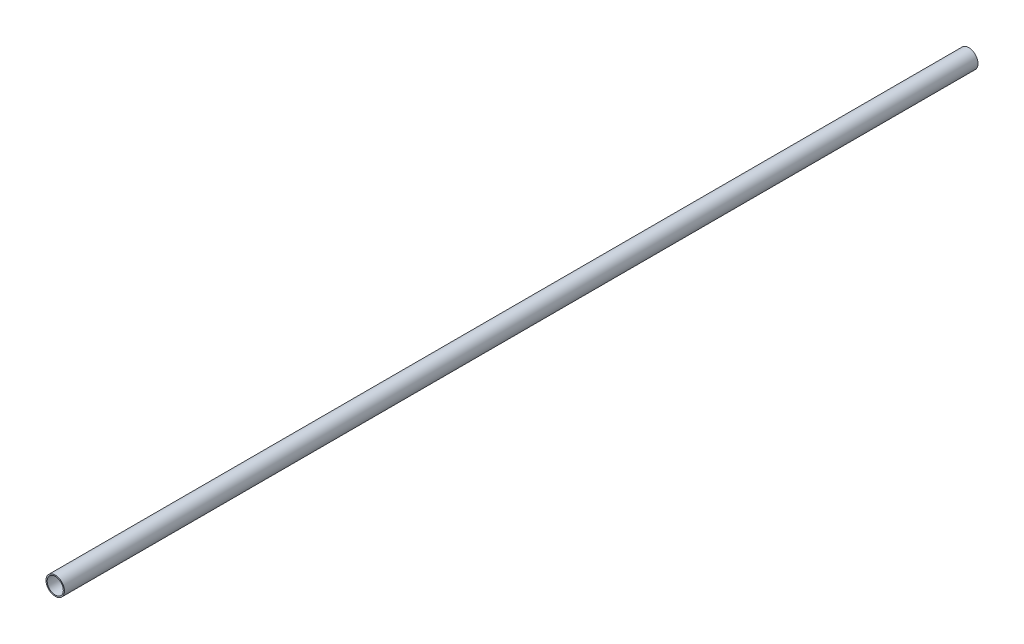
SolidWorks part; units mm, degrees
material "AISI Type 316L stainless steel"
ref_plane "Front Plane" through (0, 0, 0) normal (0, 0, 1) x (1, 0, 0)
ref_plane "Top Plane" through (0, 0, 0) normal (0, 1, 0) x (1, 0, 0)
ref_plane "Right Plane" through (0, 0, 0) normal (1, 0, 0) x (0, 0, -1)
sketch "Extrude sketch 1" plane through (0, 0, 0) normal (0, 0, 1) x (1, 0, 0)
  circle A0 centre (0, 0) radius 30.15
  circle A1 centre (0, 0) radius 26.24
  dimension "D1" = 52.48
  dimension "D2" = 60.3
extrude "Extrude 1" add sketch "Extrude sketch 1" along normal blind 2978 from offset 196.789 separate body
